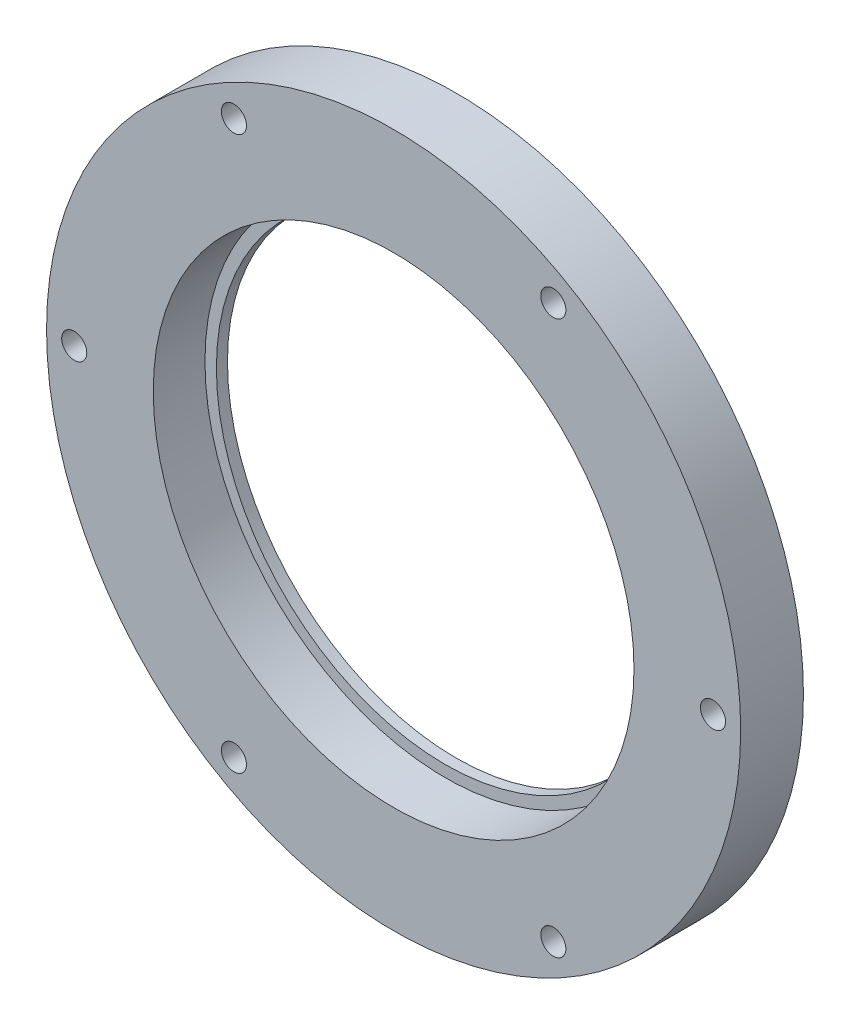
SolidWorks part; units mm, degrees
ref_plane "Front Plane" through (0, 0, 0) normal (0, 0, 1) x (1, 0, 0)
ref_plane "Top Plane" through (0, 0, 0) normal (0, 1, 0) x (1, 0, 0)
ref_plane "Right Plane" through (0, 0, 0) normal (1, 0, 0) x (0, 0, -1)
sketch "Sketch1" plane through (0, 0, 0) normal (0, 0, 1) x (1, 0, 0)
  circle A0 centre (0, 0) radius 47
  dimension "D1" = 94
extrude "Boss-Extrude2" add sketch "Sketch1" along normal blind 8.5
sketch "Sketch2" plane through (0, 0, 8.5) normal (0, 0, 1) x (1, 0, 0)
  circle A0 centre (0, 0) radius 32.55
  dimension "D1" = 65.1
extrude "Cut-Extrude1" cut sketch "Sketch2" against normal blind 7
sketch "Sketch3" plane through (0, 0, 1.5) normal (0, 0, 1) x (1, 0, 0)
  circle A0 centre (0, 0) radius 31
  dimension "D1" = 62
extrude "Brain" cut sketch "Sketch3" against normal through all contours A0
sketch "Sketch4" plane through (0, 0, 0) normal (0, 0, 1) x (1, 0, 0)
  circle A0 centre (-43.25, 0) radius 1.7
  circle A1 centre (-21.625, 37.4556) radius 1.7
  circle A2 centre (21.625, 37.4556) radius 1.7
  circle A3 centre (43.25, 0) radius 1.7
  circle A4 centre (21.625, -37.4556) radius 1.7
  circle A5 centre (-21.625, -37.4556) radius 1.7
  point P15 (0, 0)
  dimension "D1" = 3.4
  dimension "D2" = 43.25
  dimension "D3" = 6
extrude "Screw Holes" cut sketch "Sketch4" along normal through all
